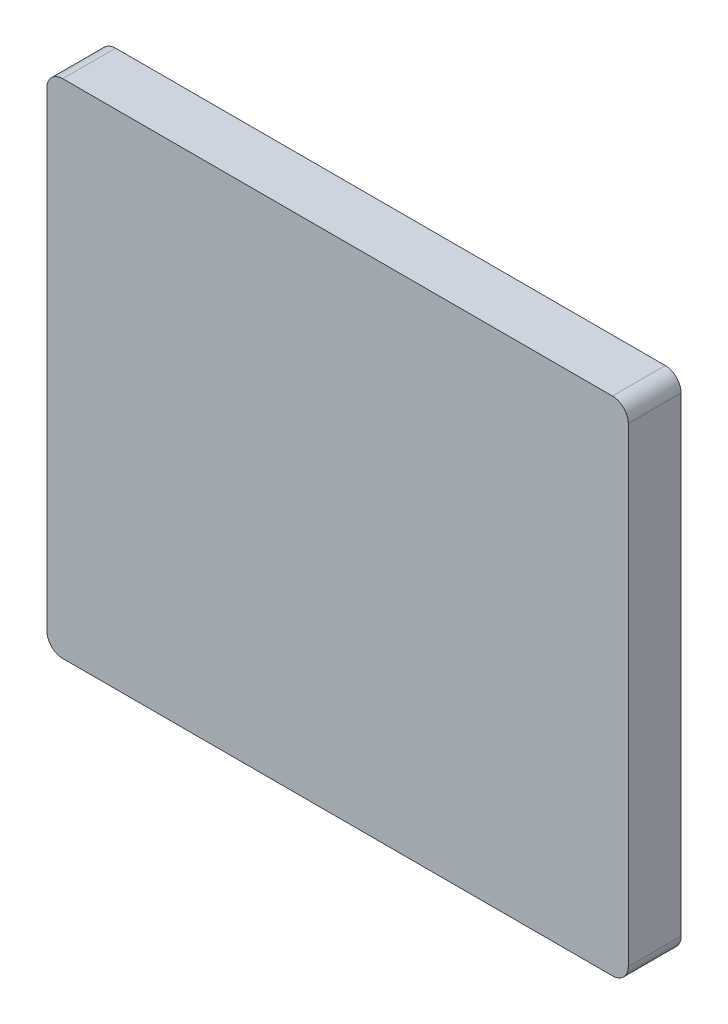
SolidWorks part; units mm, degrees
ref_plane "Front Plane" through (0, 0, 0) normal (0, 0, 1) x (1, 0, 0)
ref_plane "Top Plane" through (0, 0, 0) normal (0, 1, 0) x (1, 0, 0)
ref_plane "Right Plane" through (0, 0, 0) normal (1, 0, 0) x (0, 0, -1)
sketch "Sketch1" plane through (0, 0, 0) normal (0, 0, 1) x (1, 0, 0)
  line L1 (-77.5182, 47.385) -> (32.4818, 47.385)
  line L2 (-77.5182, 47.385) -> (-77.5182, -47.615)
  line L3 (-77.5182, -47.615) -> (32.4818, -47.615)
  line L4 (32.4818, 47.385) -> (32.4818, -47.615)
  dimension "D1" = 95
  dimension "D2" = 110
extrude "Boss-Extrude2" add sketch "Sketch1" against normal blind 10
fillet "Fillet1" radius 3 4 edges at (-77.5182, 47.385, -5) (32.4818, 47.385, -5) (32.4818, -47.615, -5) (-77.5182, -47.615, -5)
